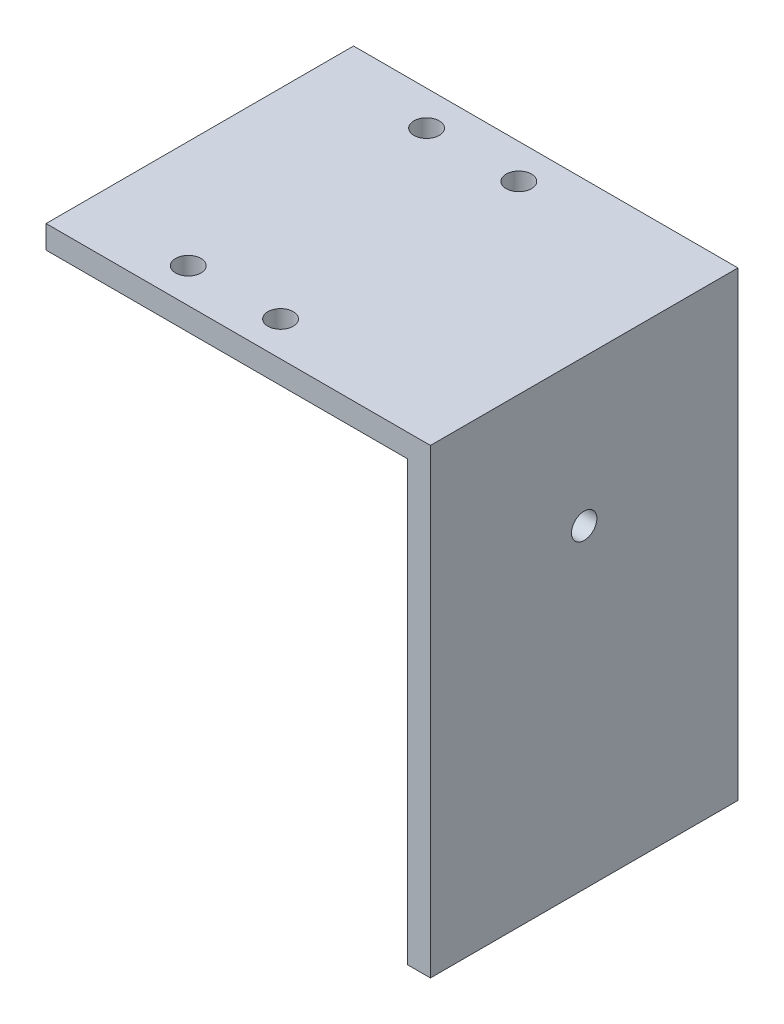
SolidWorks part; units mm, degrees
ref_plane "前视基准面" through (0, 0, 0) normal (0, 0, 1) x (1, 0, 0)
ref_plane "上视基准面" through (0, 0, 0) normal (0, 1, 0) x (1, 0, 0)
ref_plane "右视基准面" through (0, 0, 0) normal (1, 0, 0) x (0, 0, -1)
sketch "草图1" plane through (0, 0, 0) normal (0, 0, 1) x (1, 0, 0)
  line L0 (0, 0) -> (50, 0)
  line L1 (50, 0) -> (50, -60)
  line L2 (0, -3) -> (47, -3)
  line L3 (47, -3) -> (47, -60)
  line L4 (47, -60) -> (50, -60)
  line L5 (0, 0) -> (0, -3)
  dimension "D1" = 50
  dimension "D3" = 60
  dimension "D2" = 3
extrude "凸台-拉伸1" add sketch "草图1" along normal blind 40
sketch "草图2" plane through (0, 0, 0) normal (0, 1, 0) x (1, 0, 0)
  line L0 (50, -40) -> (50, 0) construction
  line L1 (14, -35.5) -> (26, -35.5) construction
  line L2 (14, -35.5) -> (14, -4.5) construction
  line L3 (14, -4.5) -> (26, -4.5) construction
  line L4 (26, -35.5) -> (26, -4.5) construction
  line L5 (14, -35.5) -> (26, -4.5) construction
  line L6 (14, -4.5) -> (26, -35.5) construction
  line L7 (20, -20) -> (50, -20) construction
  line L8 (0, -40) -> (0, 0) construction
  circle A0 centre (14, -4.5) radius 1.65
  circle A1 centre (14, -35.5) radius 1.65
  circle A2 centre (26, -4.5) radius 1.65
  circle A3 centre (26, -35.5) radius 1.65
  point P0 (20, -20)
  dimension "D4" = 3.3
  dimension "D1" = 24
  dimension "D2" = 12
  dimension "D3" = 31
extrude "切除-拉伸1" cut sketch "草图2" against normal blind 10
sketch "草图3" plane through (50, 0, 0) normal (1, 0, 0) x (0, 0, -1)
  line L0 (-20, 0) -> (-20, -62.884) construction
  line L1 (-40, 0) -> (0, 0) construction
  circle A0 centre (-20, -19.05) radius 1.65
  dimension "D1" = 3.3
  dimension "D2" = 19.05
extrude "切除-拉伸2" cut sketch "草图3" against normal blind 10
